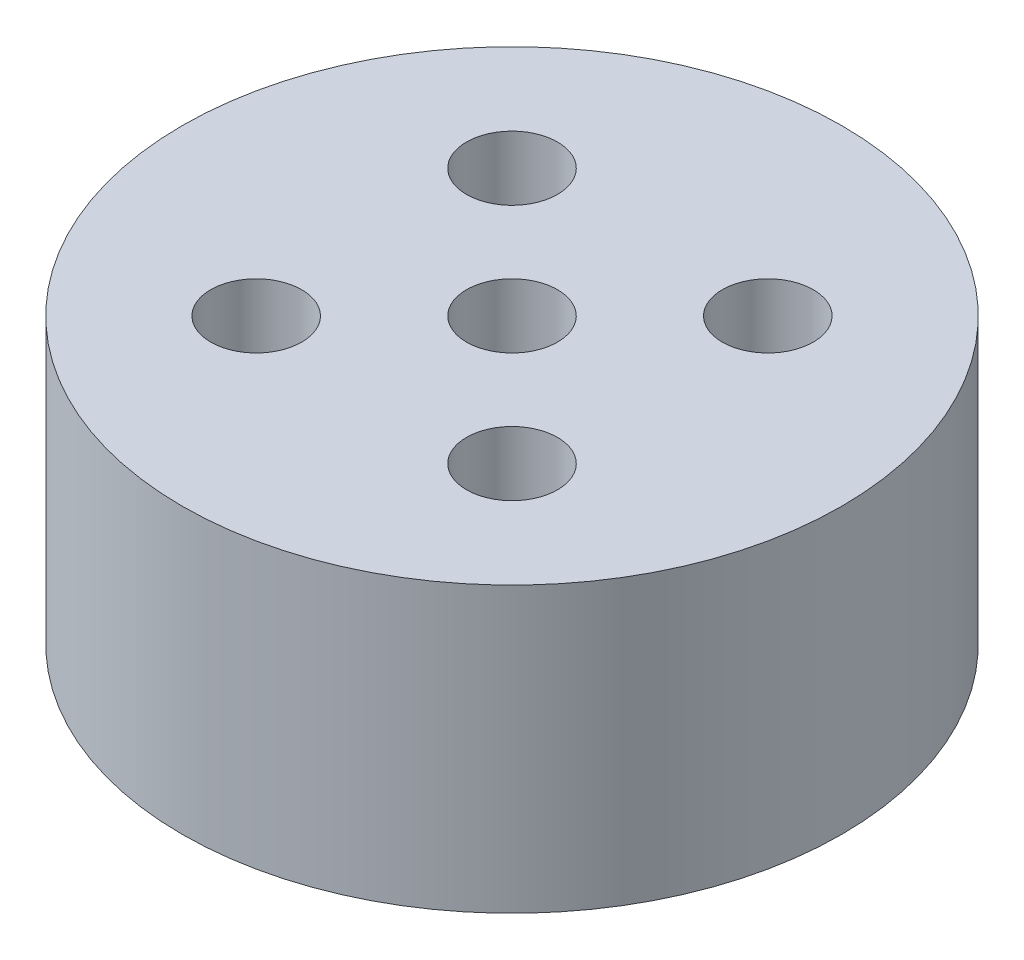
SolidWorks part; units mm, degrees
ref_plane "Front Plane" through (0, 0, 0) normal (0, 0, 1) x (1, 0, 0)
ref_plane "Top Plane" through (0, 0, 0) normal (0, 1, 0) x (1, 0, 0)
ref_plane "Right Plane" through (0, 0, 0) normal (1, 0, 0) x (0, 0, -1)
sketch "Sketch1" plane through (0, 0, 0) normal (0, 1, 0) x (1, 0, 0)
  circle A0 centre (-14.7209, 5.3871) radius 14.732
  dimension "D1" = 29.464
extrude "Boss-Extrude1" add sketch "Sketch1" along normal blind 12.7
sketch "Sketch2" plane through (0, 12.7, 0) normal (0, 1, 0) x (1, 0, 0)
  line L1 (-20.4359, -0.3279) -> (-9.0059, -0.3279) construction
  line L2 (-20.4359, -0.3279) -> (-20.4359, 11.1021) construction
  line L3 (-20.4359, 11.1021) -> (-9.0059, 11.1021) construction
  line L4 (-9.0059, -0.3279) -> (-9.0059, 11.1021) construction
  line L5 (-20.4359, -0.3279) -> (-9.0059, 11.1021) construction
  line L6 (-20.4359, 11.1021) -> (-9.0059, -0.3279) construction
  circle A0 centre (-9.0059, -0.3279) radius 2.032
  circle A1 centre (-9.0059, 11.1021) radius 2.032
  circle A2 centre (-20.4359, 11.1021) radius 2.032
  circle A3 centre (-20.4359, -0.3279) radius 2.032
  circle A4 centre (-14.7209, 5.3871) radius 2.032
  point P0 (-14.7209, 5.3871)
  dimension "D1" = 4.064
  dimension "D2" = 11.43
  dimension "D3" = 11.43
extrude "Cut-Extrude1" cut sketch "Sketch2" against normal blind 12.7
